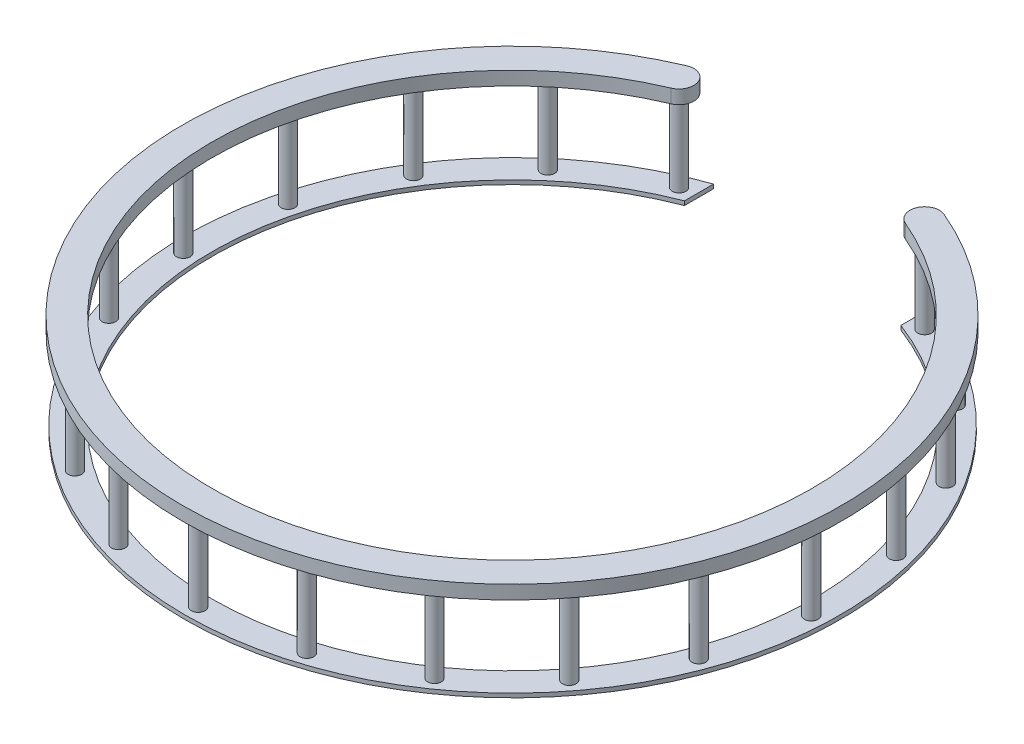
SolidWorks part; units mm, degrees
ref_plane "Front Plane" through (0, 0, 0) normal (0, 0, 1) x (1, 0, 0)
ref_plane "Top Plane" through (0, 0, 0) normal (0, 1, 0) x (1, 0, 0)
ref_plane "Right Plane" through (0, 0, 0) normal (1, 0, 0) x (0, 0, -1)
sketch "Sketch2" plane through (0, 0, 0) normal (0, 1, 0) x (1, 0, 0)
  line L0 (0, 12000) -> (0, 9000) construction
  circle A0 centre (0, 0) radius 12000
  dimension "D1" = 24000
  dimension "D2" = 3000
extrude "Boss-Extrude1" add sketch "Sketch2" along normal blind 150
sketch "Sketch3" plane through (0, 150, 0) normal (0, 1, 0) x (1, 0, 0)
  line L0 (-3968.627, 9000) -> (-7937.2539, 9000)
  line L3 (-3968.627, 9000) -> (-3968.627, 11324.7517)
  line L4 (3968.627, 9000) -> (7937.2539, 9000)
  line L5 (3968.627, 9000) -> (3968.627, 11324.7517)
  line L6 (0, 0) -> (0, 12000) construction
  circle A0 centre (0, 0) radius 12000 construction
  arc A2 (7937.2539, 9000) -> (3968.627, 11324.7517) centre (0, 0) ccw
  arc A3 (-7937.2539, 9000) -> (-3968.627, 11324.7517) centre (0, 0) cw
  circle A4 centre (0, 0) radius 12000 construction
sketch "Sketch4" plane through (0, 150, 0) normal (0, 1, 0) x (1, 0, 0)
  circle A2 centre (0, 0) radius 11000
  circle A3 centre (0, 0) radius 11000
  dimension "D1" = 1000
extrude "Cut-Extrude1" cut sketch "Sketch4" against normal blind 2000
sketch "Sketch5" plane through (0, 150, 0) normal (0, 1, 0) x (1, 0, 0)
  line L0 (0, -12000) -> (0, -11000) construction
  circle A1 centre (0, 0) radius 12000 construction
  circle A2 centre (0, 0) radius 11000 construction
  circle A3 centre (0, -11500) radius 250
  dimension "D1" = 500
extrude "Boss-Extrude4" add sketch "Sketch5" along normal blind 3000
pattern_circular "CirPattern3" count 10 every 17.444 about axis through (0, 0, 0) along (0, 1, 0) of "Boss-Extrude4"
sketch "Sketch8" plane through (0, 150, 0) normal (0, 1, 0) x (1, 0, 0)
  line L1 (-3968.627, 9000) -> (3936.4505, 9000)
  line L2 (-3968.627, 9000) -> (-3968.627, 12194.4392)
  line L3 (-3968.627, 12194.4392) -> (3936.4505, 12194.4392)
  line L4 (3936.4505, 9000) -> (3936.4505, 12194.4392)
extrude "Cut-Extrude3" cut sketch "Sketch8" along normal blind 5000 and the other way blind 3000
ref_plane "Plane2" through (0, 3150, 0) normal (0, 1, 0) x (1, 0, 0)
sketch "Sketch9" plane through (0, 3150, 0) normal (0, 1, 0) x (1, 0, 0)
  arc A0 (-4493.408, 10585.8058) -> (4493.408, 10585.8058) centre (0, -19.9817) ccw construction
  arc A1 (-4703.7816, 11082.3505) -> (4703.7816, 11082.3505) centre (0, -19.9817) ccw
  arc A2 (-4283.0344, 10089.2611) -> (4283.0344, 10089.2611) centre (0, -19.9817) ccw
  arc A3 (-4283.0344, 10089.2611) -> (-4703.7816, 11082.3505) centre (-4493.408, 10585.8058) ccw
  arc A4 (4703.7816, 11082.3505) -> (4283.0344, 10089.2611) centre (4493.408, 10585.8058) ccw
  point P3 (0, -11538.3775)
extrude "Boss-Extrude6" add sketch "Sketch9" along normal blind 500
